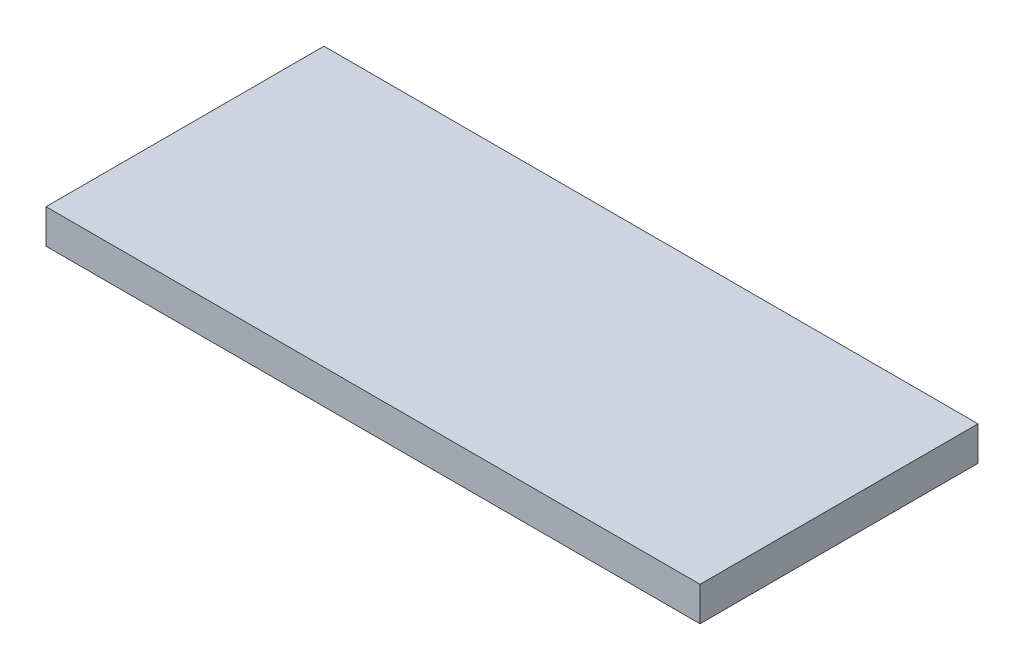
SolidWorks part; units mm, degrees
material "Plain Carbon Steel"
ref_plane "Front Plane" through (0, 0, 0) normal (0, 0, 1) x (1, 0, 0)
ref_plane "Top Plane" through (0, 0, 0) normal (0, 1, 0) x (1, 0, 0)
ref_plane "Right Plane" through (0, 0, 0) normal (1, 0, 0) x (0, 0, -1)
sketch "Sketch1" plane through (0, 0, 0) normal (0, 1, 0) x (1, 0, 0)
  line L1 (0, 0) -> (59.76, 0)
  line L2 (0, 0) -> (0, 25.4)
  line L3 (0, 25.4) -> (59.76, 25.4)
  line L4 (59.76, 0) -> (59.76, 25.4)
  dimension "D1" = 59.76
  dimension "D2" = 25.4
extrude "Boss-Extrude1" add sketch "Sketch1" along normal blind 3.125
